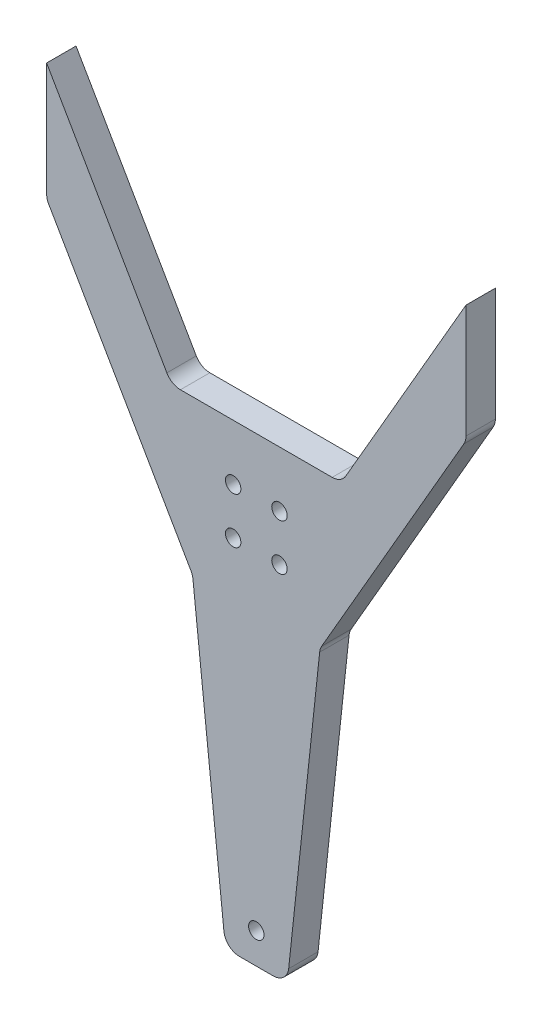
SolidWorks part; units mm, degrees
ref_plane "Plan de face" through (0, 0, 0) normal (0, 0, 1) x (1, 0, 0)
ref_plane "Plan de dessus" through (0, 0, 0) normal (0, 1, 0) x (1, 0, 0)
ref_plane "Plan de droite" through (0, 0, 0) normal (1, 0, 0) x (0, 0, -1)
sketch "Sketch1" plane through (0, 0, 0) normal (0, 0, 1) x (1, 0, 0)
  line L18 (-27.5105, 50) -> (27.5105, 50)
  line L19 (27.5105, 50) -> (67.925, 120)
  line L21 (67.925, 81.9) -> (20.64, 0)
  line L23 (20.64, 0) -> (10, -99.4323)
  line L24 (10, -99.4323) -> (-10, -99.4323)
  line L25 (-10, -99.4323) -> (-20.64, 0)
  line L26 (-20.64, 0) -> (-67.925, 81.9)
  line L28 (-67.925, 120) -> (-27.5105, 50)
  line L29 (-20.64, 0) -> (20.64, 0) construction
  line L30 (-67.925, 120) -> (-67.925, 81.9)
  line L31 (67.925, 120) -> (67.925, 81.9)
  point P12 (0, 50)
  point P18 (0, -99.4323)
  dimension "D1" = 41.28
  dimension "D2" = 19.05
  dimension "D3" = 60
  dimension "D4" = 120
  dimension "D5" = 100
  dimension "D6" = 50
  dimension "D7" = 20
  dimension "D8" = 19.05
  dimension "D9" = 67.925
extrude "Boss-Extrude1" add sketch "Sketch1" along normal blind 9.525
fillet "Fillet1" radius 5.08 8 edges at (-10, -99.4323, 4.7625) (10, -99.4323, 4.7625) (-27.5105, 50, 4.7625) (27.5105, 50, 4.7625) (20.64, 0, 4.7625) (-20.64, 0, 4.7625) (67.925, 81.9, 4.7625) (-67.925, 81.9, 4.7625)
hole_wizard "Ø5.0mm Dowel Hole1" positions "Sketch12" profile "Sketch13" hole size "Ø5.0" standard "ANSI Metric" end condition through all
sketch "Sketch12" plane through (0, 0, 0) normal (0, 0, -1) x (-1, 0, 0)
  line L0 (-24.5775, 50) -> (24.5775, 50) construction
  line L6 (7.5, 31.9657) -> (-7.5, 16.9657) construction
  line L9 (7.5, 16.9657) -> (-7.5, 31.9657) construction
  line L11 (26.9323, 27.5) -> (27.187, 27.4966) construction
  line L12 (-24.5775, 50) -> (-24.5775, -1.0687) construction
  point P0 (-7.5, 31.9657)
  point P2 (7.5, 31.9657)
  point P4 (-7.5, 16.9657)
  point P6 (7.5, 16.9657)
  point P52 (0, 50)
  point P53 (0, 24.4657)
  point P61 (-24.5775, 24.4657)
  dimension "D2" = 15
  dimension "D3" = 15
sketch "Sketch13" plane through (7.5, 31.9657, 0) normal (1, 0, 0) x (0, 1, 0)
  line L0 (0, 0) -> (0, 9.525)
  line L1 (0, 9.525) -> (2.5, 9.525)
  line L2 (2.5, 9.525) -> (2.5, 0)
  line L5 (2.5, 0) -> (0, 0)
  line L11 (0, -6.35) -> (0, 107.95) construction
  dimension "Thru Hole Dia." = 5
  dimension "Thru Hole Depth" = 9.525
sketch "Sketch14" plane through (0, 0, 9.525) normal (0, 0, 1) x (1, 0, 0)
  line L0 (-5.4346, -99.4323) -> (5.4346, -99.4323) construction
  circle A0 centre (0, -89.4323) radius 2.5
  dimension "D1" = 5
  dimension "D2" = 10
extrude "Cut-Extrude1" cut sketch "Sketch14" against normal through all
